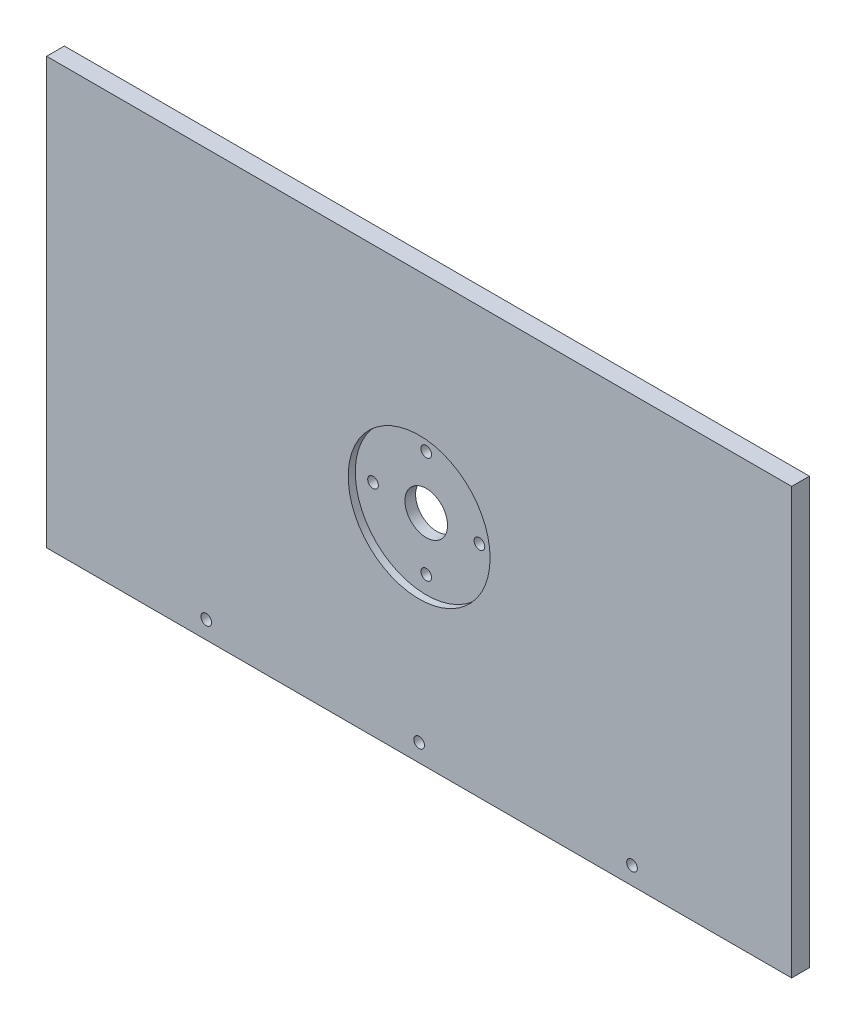
SolidWorks part; units mm, degrees
ref_plane "Front Plane" through (0, 0, 0) normal (0, 0, 1) x (1, 0, 0)
ref_plane "Top Plane" through (0, 0, 0) normal (0, 1, 0) x (1, 0, 0)
ref_plane "Right Plane" through (0, 0, 0) normal (1, 0, 0) x (0, 0, -1)
sketch "Sketch1" plane through (0, 0, 0) normal (0, 0, 1) x (1, 0, 0)
  line L0 (0, 0) -> (210, 0)
  line L1 (210, 0) -> (210, -120)
  line L2 (210, -120) -> (0, -120)
  line L3 (0, -120) -> (0, 0)
extrude "Boss-Extrude1" add sketch "Sketch1" along normal blind 5
sketch "Sketch2" plane through (0, 0, 5) normal (0, 0, 1) x (1, 0, 0)
  line L0 (0, -60) -> (210, -60)
  line L1 (0, 0) -> (0, -120) construction
  line L2 (210, -120) -> (210, 0) construction
  circle A0 centre (105, -60) radius 20
extrude "Cut-Extrude1" cut sketch "Sketch2" against normal blind 2 contours L0 A0 | L0 A0
sketch "Sketch3" plane through (0, 0, 3) normal (0, 0, 1) x (1, 0, 0)
  circle A0 centre (105, -60) radius 15
  circle A1 centre (105, -45) radius 1.5
  circle A2 centre (120, -60) radius 1.5
  circle A3 centre (105, -75) radius 1.5
  circle A4 centre (90, -60) radius 1.5
extrude "Cut-Extrude3" cut sketch "Sketch3" against normal blind 5 contours A4 | A1 | A2 | A3
sketch "Sketch4" plane through (0, 0, 3) normal (0, 0, 1) x (1, 0, 0)
  circle A0 centre (105, -60) radius 6
extrude "Cut-Extrude4" cut sketch "Sketch4" against normal blind 5
sketch "Sketch5" plane through (0, 0, 5) normal (0, 0, 1) x (1, 0, 0)
  line L0 (105, -120) -> (105, -115)
  line L1 (0, -120) -> (210, -120) construction
  line L2 (105, -115) -> (165, -115)
  line L3 (105, -115) -> (45, -115)
  circle A0 centre (45, -115) radius 1.5
  circle A1 centre (105, -115) radius 1.5
  circle A2 centre (165, -115) radius 1.5
extrude "Cut-Extrude5" cut sketch "Sketch5" against normal blind 10 contours A0 | A1 | A2
